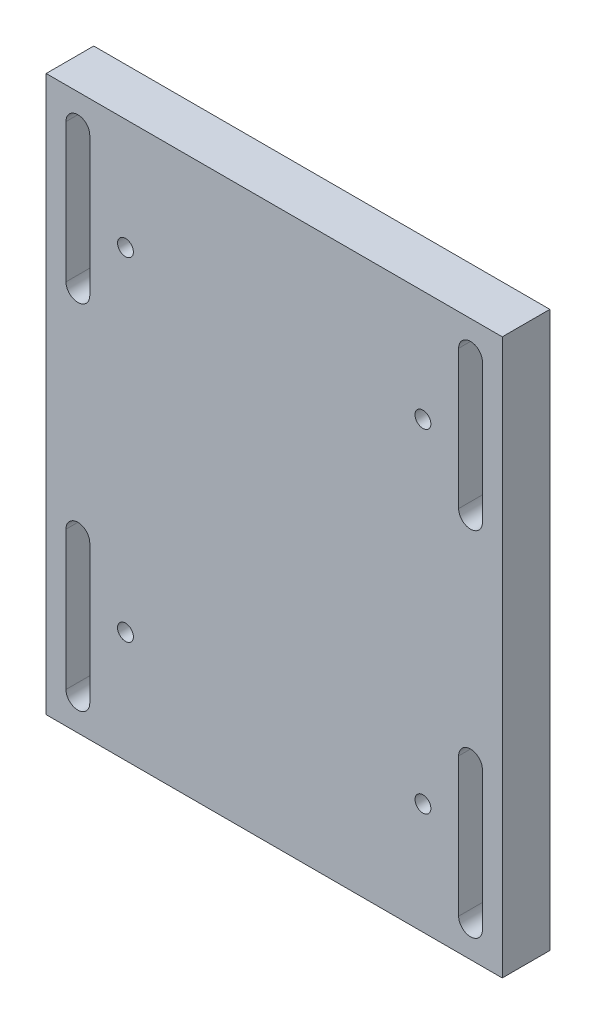
SolidWorks part; units mm, degrees
ref_plane "Front Plane" through (0, 0, 0) normal (0, 0, 1) x (1, 0, 0)
ref_plane "Top Plane" through (0, 0, 0) normal (0, 1, 0) x (1, 0, 0)
ref_plane "Right Plane" through (0, 0, 0) normal (1, 0, 0) x (0, 0, -1)
sketch "Sketch1" plane through (0, 0, 0) normal (0, 0, 1) x (1, 0, 0)
  line L1 (-57.5, 70) -> (57.5, 70)
  line L2 (-57.5, 70) -> (-57.5, -70)
  line L3 (-57.5, -70) -> (57.5, -70)
  line L4 (57.5, 70) -> (57.5, -70)
  line L5 (-57.5, 70) -> (57.5, -70) construction
  line L6 (-57.5, -70) -> (57.5, 70) construction
  point P0 (0, 0)
  dimension "D1" = 140
  dimension "D2" = 115
extrude "Boss-Extrude1" add sketch "Sketch1" along normal mid plane 12
sketch "Sketch4" plane through (0, 0, 6) normal (0, 0, 1) x (1, 0, 0)
  line L0 (57.5, -70) -> (57.5, 70) construction
  line L1 (57.5, 70) -> (-57.5, 70) construction
  line L2 (52.5, 62) -> (52.5, 27)
  line L4 (46.5, 27) -> (46.5, 62)
  arc A0 (52.5, 62) -> (46.5, 62) centre (49.5, 62) ccw
  arc A1 (46.5, 27) -> (52.5, 27) centre (49.5, 27) ccw
  dimension "D1" = 3
  dimension "D3" = 8
  dimension "D5" = 35
  dimension "D2" = 8
extrude "Cut-Extrude1" cut sketch "Sketch4" against normal up to surface (12 mm away) up to face at (0, 0, -6)
sketch "Sketch5" plane through (0, 0, 6) normal (0, 0, 1) x (1, 0, 0)
  line L0 (57.5, 70) -> (-57.5, 70) construction
  line L1 (57.5, -70) -> (57.5, 70) construction
  circle A0 centre (37.5, 42) radius 2
  dimension "D1" = 28
  dimension "D2" = 4
  dimension "D3" = 20
extrude "Cut-Extrude2" cut sketch "Sketch5" against normal up to surface (12 mm away) up to face at (49.5, 44.5, -6)
mirror "Mirror1" about plane through (0, 0, 0) normal (0, 1, 0) of "Cut-Extrude2", "Cut-Extrude1"
mirror "Mirror2" about plane through (0, 0, 0) normal (1, 0, 0) of "Mirror1", "Cut-Extrude1", "Cut-Extrude2"
